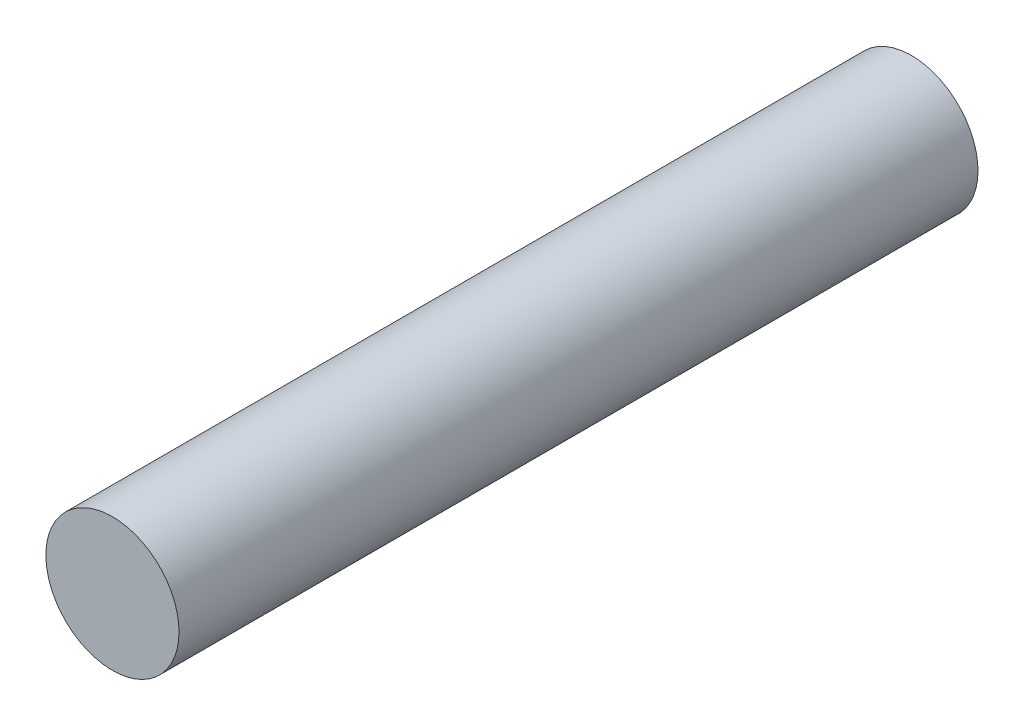
SolidWorks part; units mm, degrees
ref_plane "Piano frontale" through (0, 0, 0) normal (0, 0, 1) x (1, 0, 0)
ref_plane "Piano superiore" through (0, 0, 0) normal (0, 1, 0) x (1, 0, 0)
ref_plane "Piano destro" through (0, 0, 0) normal (1, 0, 0) x (0, 0, -1)
sketch "Schizzo1" plane through (0, 0, 0) normal (0, 0, 1) x (1, 0, 0)
  circle A0 centre (0, 0) radius 2
  dimension "D1" = 4
extrude "Estrusione-Estrusione1" add sketch "Schizzo1" along normal blind 24
